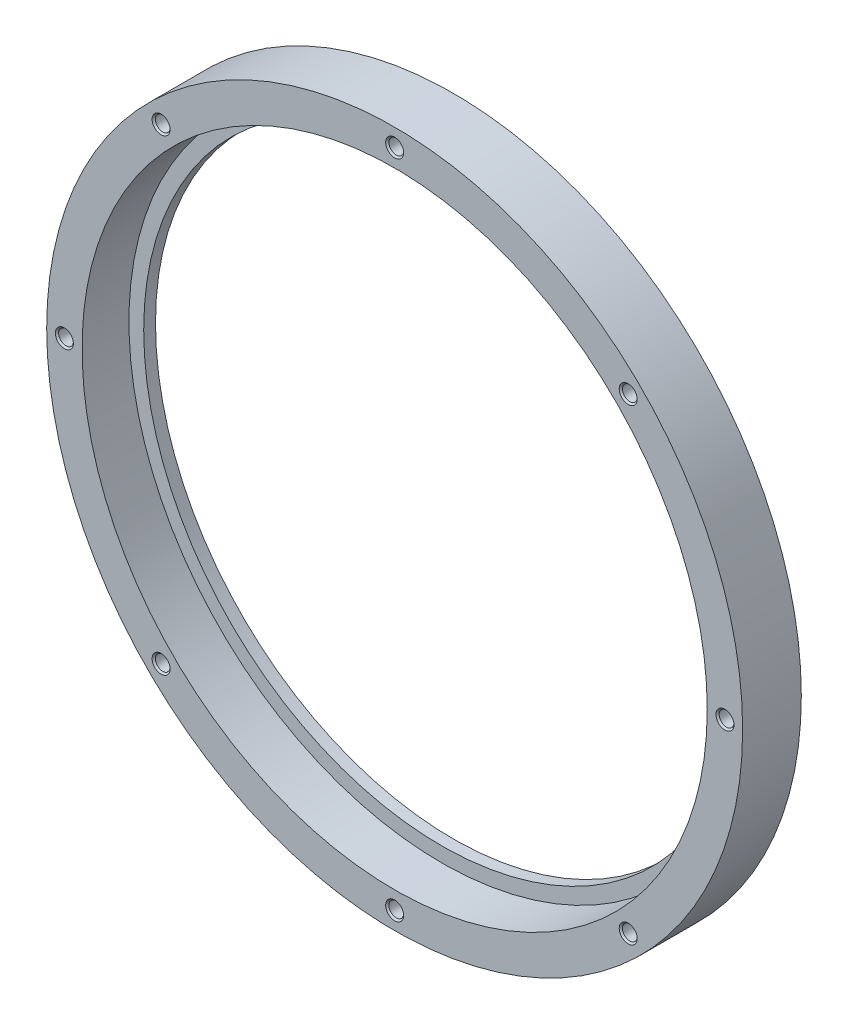
SolidWorks part; units mm, degrees
material "6061 合金"
ref_plane "前视基准面" through (0, 0, 0) normal (0, 0, 1) x (1, 0, 0)
ref_plane "上视基准面" through (0, 0, 0) normal (0, 1, 0) x (1, 0, 0)
ref_plane "右视基准面" through (0, 0, 0) normal (1, 0, 0) x (0, 0, -1)
other "Configuration Table"
sketch "草图1" plane through (0, 0, 0) normal (0, 0, 1) x (1, 0, 0)
  circle A0 centre (0, 0) radius 53
  circle A1 centre (0, 0) radius 59
  dimension "D1" = 106
  dimension "D2" = 6
extrude "凸台-拉伸1" add sketch "草图1" along normal mid plane 7.95
sketch "草图2" plane through (0, 0, -3.975) normal (0, 0, -1) x (-1, 0, 0)
  circle A0 centre (0, 0) radius 50.5
  circle A1 centre (0, 0) radius 53 construction
  circle A2 centre (0, 0) radius 59 construction
  circle A3 centre (0, 0) radius 59
  dimension "D1" = 2.5
extrude "凸台-拉伸2" add sketch "草图2" along normal blind 2
sketch "草图3" plane through (0, 0, 3.975) normal (0, 0, 1) x (1, 0, 0)
  circle A0 centre (0, 0) radius 56 construction
  circle A1 centre (0, 0) radius 59 construction
  dimension "D1" = 3
hole_wizard "M3 螺纹孔1" positions "草图4" profile "草图5" tap size "M3" standard "GB" end condition through all
sketch "草图4" plane through (0, 0, 3.975) normal (0, 0, 1) x (1, 0, 0)
  circle A0 centre (0, 0) radius 56 construction
  point P0 (0, 56)
sketch "草图5" plane through (0, 56, 3.975) normal (1, 0, 0) x (0, -1, 0)
  line L0 (0, 0) -> (0, 9.95)
  line L1 (0, 9.95) -> (1.25, 9.95)
  line L2 (1.25, 9.95) -> (1.25, 0.275)
  line L3 (1.25, 0.275) -> (1.525, 0)
  line L5 (1.525, 0) -> (0, 0)
  line L6 (-1.25, 0.275) -> (-1.525, 0) construction
  line L11 (0, -6.35) -> (0, 107.95) construction
  dimension "通孔螺纹孔钻头直径" = 2.5
  dimension "通孔螺纹孔钻头深度" = 9.95
  dimension "近端锥形沉头孔直径" = 3.05
  dimension "近端锥形沉头孔角度" = 90
cosmetic thread "孔螺蚊线1" parameters "D2"=3
pattern_circular "阵列(圆周)1" count 8 over 360 about axis through (0, 0, 0) along (0, 0, 1) of "M3 螺纹孔1"
